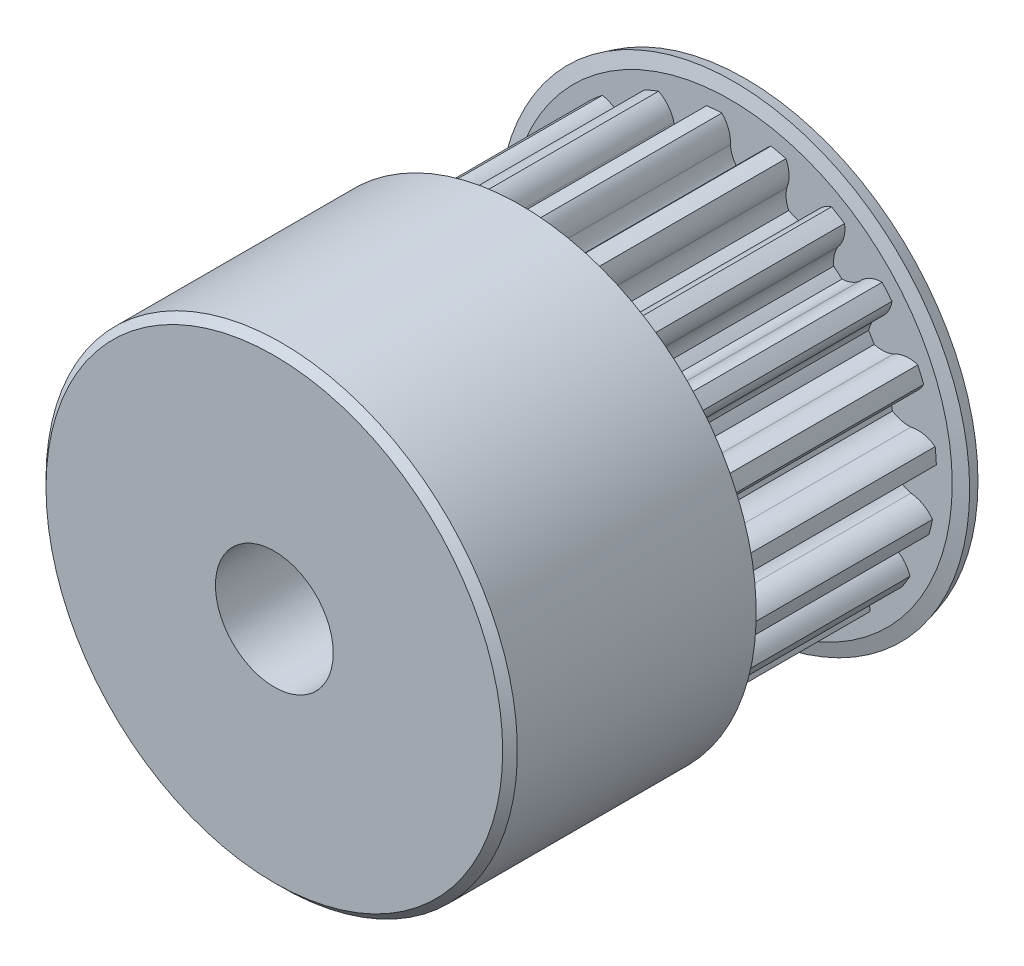
SolidWorks part; units mm, degrees
ref_plane "Front Plane" through (0, 0, 0) normal (0, 0, 1) x (1, 0, 0)
ref_plane "Top Plane" through (0, 0, 0) normal (0, 1, 0) x (1, 0, 0)
ref_plane "Right Plane" through (0, 0, 0) normal (1, 0, 0) x (0, 0, -1)
sketch "Sketch1" plane through (0, 0, 0) normal (0, 0, 1) x (1, 0, 0)
  circle A0 centre (0, 0) radius 7
  dimension "D1" = 14
extrude "Boss-Extrude1" add sketch "Sketch1" along normal blind 7
sketch "Sketch2" plane through (0, 0, 7) normal (0, 0, 1) x (1, 0, 0)
  circle A0 centre (0, 0) radius 6.365
  circle A1 centre (0, 0) radius 5.62
  circle A2 centre (0, 6.365) radius 1
  circle A3 centre (-0.9969, 6.2864) radius 1
  circle A4 centre (0.9969, 6.2864) radius 1
  circle A5 centre (1.9692, 6.0527) radius 1
  circle M1 centre (0, 0) radius 7
  dimension "D1" = 12.73
  dimension "D2" = 11.24
extrude "Cut-Extrude1" cut sketch "Sketch2" against normal blind 7 contours A5 A2 M1 | A4 A0 A2 M1 | A4 A3 M1 | A5 A0 A3 A4 A1 A2
pattern_circular "CirPattern1" count 20 over 360 about axis through (0, 0, 0) along (0, 0, 1) of "Cut-Extrude1"
sketch "Sketch3" plane through (0, 0, 7) normal (0, 0, 1) x (1, 0, 0)
  circle A0 centre (0, 0) radius 2.5
extrude "Cut-Extrude2" cut sketch "Sketch3" against normal blind 7
sketch "Sketch4" plane through (0, 0, 0) normal (1, 0, 0) x (0, 0, -1)
  line L0 (0, 0) -> (0, 8) construction
  line L1 (0, 0) -> (0, -8) construction
  line L2 (0, -6.994) -> (0.4, -6.994) construction
  line L3 (0, 0) -> (0, -2.4987) construction
  line L4 (0, -7.5328) -> (0.1252, -8)
  line L5 (0.1252, -8) -> (0.5116, -7.8965)
  line L6 (0.5116, -7.8965) -> (0.4, -7.4801)
  line L7 (0, -2.4987) -> (0, -7.5328)
  line L8 (0, -2.4987) -> (0.4, -2.4987)
  line L9 (0.4, -2.4987) -> (0.4, -7.4801)
  line L10 (0, 0) -> (2.2534, 0) construction
  dimension "D1" = 15
revolve "Revolve3" add sketch "Sketch4" angle 360 about L10
sketch "Sketch7" plane through (0, 0, 0) normal (1, 0, 0) x (0, 0, -1)
  line L0 (0, 0) -> (-7, -0.0031) construction
  line L1 (-7, -0.0031) -> (-7, 3.3706) construction
  line L2 (-7, 3.6489) -> (-7, 3.0923) construction
  line L3 (-7, 3.3706) -> (-7, 7.5328)
  line L4 (0.1252, 8) -> (-7, 8) construction
  line L5 (0, 7.5328) -> (-7, 7.5328) construction
  line L6 (-7, 7.5328) -> (-7.1252, 8)
  line L7 (-7, 8) -> (-7.1252, 8) construction
  line L8 (-7.1252, 8) -> (-15.2352, 8)
  line L9 (-7, 3.3706) -> (-15.4852, 3.3706)
  line L10 (-15.4852, 3.3706) -> (-15.4852, 7.75)
  line L11 (-15.2352, 8) -> (-15.4852, 7.75)
  line L12 (-7, -0.0031) -> (-8.9131, -0.0031) construction
  point P15 (-15.4852, 8)
  dimension "D1" = 15
revolve "Revolve4" add sketch "Sketch7" angle 360 about L12
sketch "Sketch8" plane through (0, 0, 15.4852) normal (0, 0, 1) x (1, 0, 0)
  circle A0 centre (0, 0) radius 2
  circle A1 centre (0, 0) radius 3.6821
extrude "Boss-Extrude2" add sketch "Sketch8" against normal blind 8
